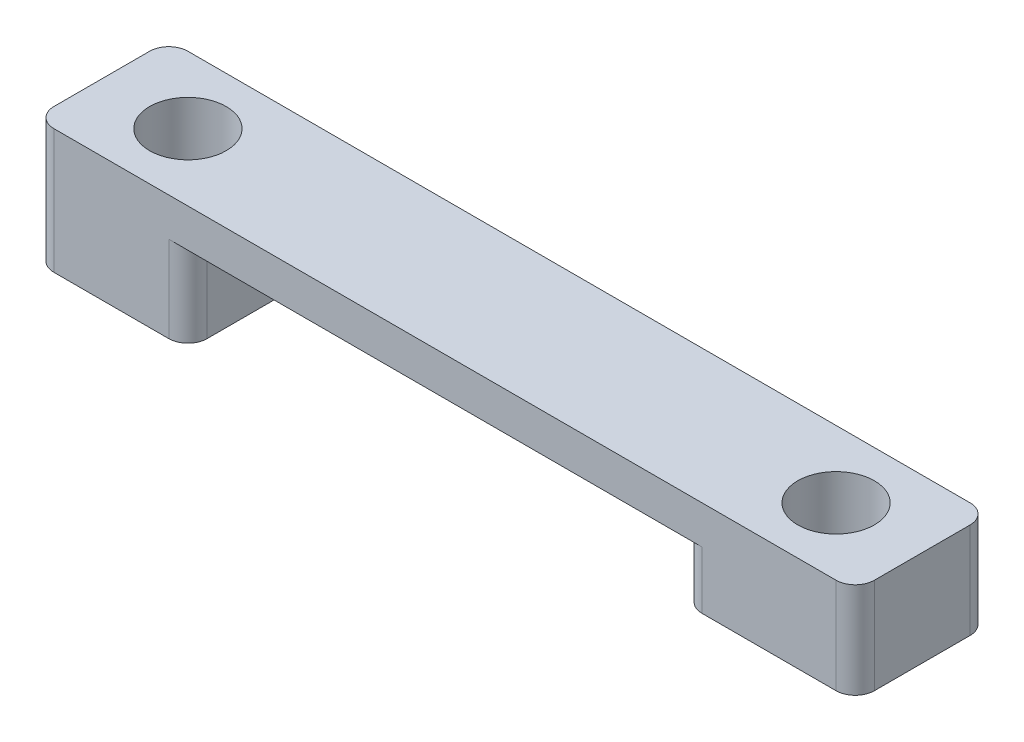
SolidWorks part; units mm, degrees
ref_plane "Front Plane" through (0, 0, 0) normal (0, 0, 1) x (1, 0, 0)
ref_plane "Top Plane" through (0, 0, 0) normal (0, 1, 0) x (1, 0, 0)
ref_plane "Right Plane" through (0, 0, 0) normal (1, 0, 0) x (0, 0, -1)
sketch "Sketch1" plane through (0, 0, 0) normal (0, 1, 0) x (1, 0, 0)
  line L0 (-16.925, 0) -> (16.925, 0) construction
  line L1 (-20.425, -3.5) -> (20.425, -3.5)
  line L2 (-21.425, -2.5) -> (-21.425, 2.5)
  line L3 (-20.425, 3.5) -> (20.425, 3.5)
  line L4 (21.425, -2.5) -> (21.425, 2.5)
  line L5 (-21.425, -3.5) -> (21.425, 3.5) construction
  line L6 (-21.425, 3.5) -> (21.425, -3.5) construction
  circle A0 centre (-16.925, 0) radius 2
  circle A1 centre (16.925, 0) radius 2
  arc A2 (20.425, 3.5) -> (21.425, 2.5) centre (20.425, 2.5) cw
  arc A3 (20.425, -3.5) -> (21.425, -2.5) centre (20.425, -2.5) ccw
  arc A4 (-20.425, -3.5) -> (-21.425, -2.5) centre (-20.425, -2.5) cw
  arc A5 (-21.425, 2.5) -> (-20.425, 3.5) centre (-20.425, 2.5) cw
  point P0 (0, 0)
  point P10 (8.9882, 0.6353)
  point P11 (0, 0)
  point P12 (-22.1298, 4.4774)
  dimension "D1" = 4
  dimension "D5" = 1
  dimension "D2" = 33.85
  dimension "D3" = 7
  dimension "D4" = 42.85
extrude "Boss-Extrude1" add sketch "Sketch1" along normal blind 2
sketch "Sketch2" plane through (0, 0, 0) normal (0, -1, 0) x (1, 0, 0)
  line L0 (-20.425, 3.5) -> (20.425, 3.5) construction
  line L1 (-14.425, -3.5) -> (-20.425, -3.5)
  line L2 (-13.425, 2.5) -> (-13.425, -2.5)
  line L3 (-14.425, 3.5) -> (-20.425, 3.5)
  line L4 (-21.425, -2.5) -> (-21.425, 2.5)
  line L5 (20.425, -3.5) -> (-20.425, -3.5) construction
  line L7 (-21.425, -2.5) -> (-21.425, 2.5) construction
  line L8 (-16.925, 3.5) -> (-16.925, -3.5) construction
  circle A0 centre (-16.925, 0) radius 2
  arc A1 (-20.425, 3.5) -> (-21.425, 2.5) centre (-20.425, 2.5) ccw construction
  arc A2 (-13.425, -2.5) -> (-14.425, -3.5) centre (-14.425, -2.5) cw
  arc A3 (-20.425, -3.5) -> (-21.425, -2.5) centre (-20.425, -2.5) cw
  arc A4 (-20.425, 3.5) -> (-21.425, 2.5) centre (-20.425, 2.5) ccw
  circle A5 centre (-16.925, 0) radius 2 construction
  arc A6 (-13.425, 2.5) -> (-14.425, 3.5) centre (-14.425, 2.5) ccw
  point P3 (0, 0)
  point P15 (-13.425, -3.5)
  point P29 (-16.925, 0)
  point P30 (-13.425, 3.5)
  point P33 (-16.925, -3.5)
  dimension "D1" = 1
extrude "Boss-Extrude2" add sketch "Sketch2" along normal blind 4.5
sketch "Sketch3" plane through (0, 0, 0) normal (0, -1, 0) x (1, 0, 0)
  line L0 (13.425, 3.5) -> (20.425, 3.5)
  line L2 (21.425, 2.5) -> (21.425, -2.5)
  line L3 (20.425, -3.5) -> (13.425, -3.5)
  line L5 (20.425, -3.5) -> (-14.425, -3.5) construction
  line L6 (21.425, 2.5) -> (21.425, -2.5) construction
  line L7 (16.925, 3.5) -> (16.925, -3.5) construction
  line L8 (12.425, 2.5) -> (12.425, -2.5)
  circle A0 centre (16.925, 0) radius 2
  circle A1 centre (16.925, 0) radius 2 construction
  arc A2 (21.425, -2.5) -> (20.425, -3.5) centre (20.425, -2.5) cw
  arc A3 (20.425, 3.5) -> (21.425, 2.5) centre (20.425, 2.5) cw
  arc A4 (13.425, 3.5) -> (12.425, 2.5) centre (13.425, 2.5) ccw
  arc A5 (12.425, -2.5) -> (13.425, -3.5) centre (13.425, -2.5) ccw
  dimension "D1" = 1
extrude "Boss-Extrude3" add sketch "Sketch3" along normal blind 3
